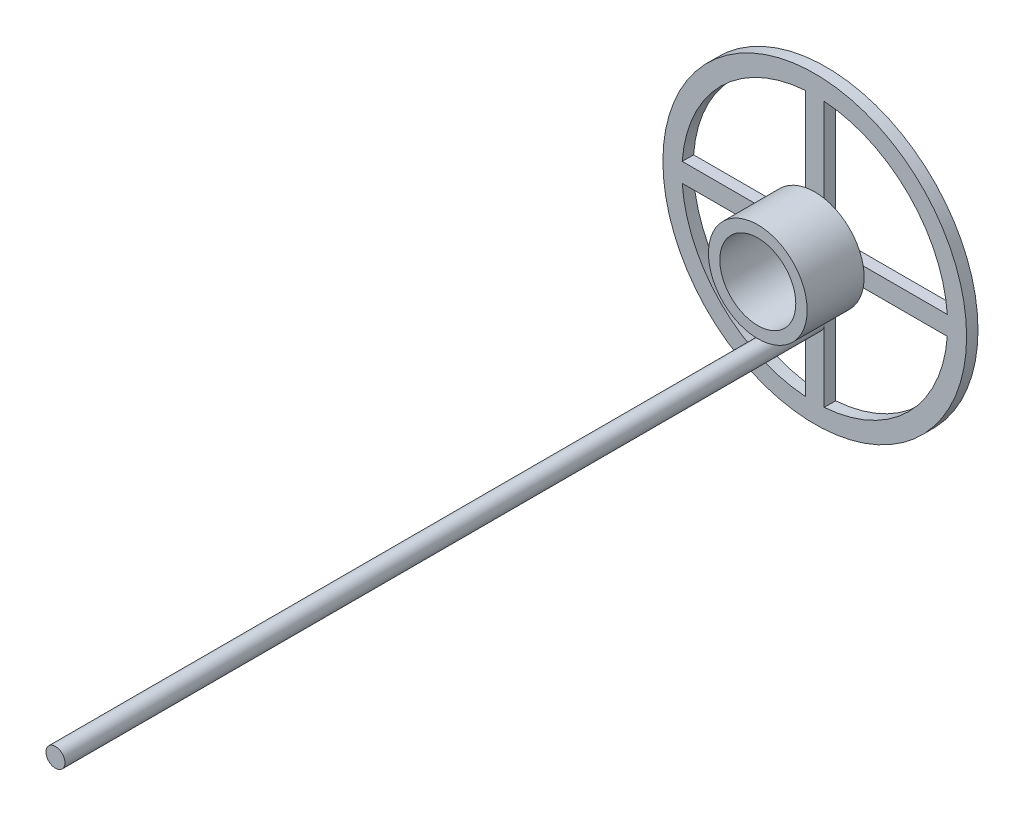
SolidWorks part; units mm, degrees
ref_plane "Alzado" through (0, 0, 0) normal (1, 0, 0) x (0, 1, 0)
ref_plane "Planta" through (0, 0, 0) normal (0, 0, 1) x (0, 1, 0)
ref_plane "Vista lateral" through (0, 0, 0) normal (0, 1, 0) x (-1, 0, 0)
sketch "Croquis1" plane through (0, 0, 0) normal (0, 0, 1) x (0, 1, 0)
  line L0 (25, -25) -> (349.106, -25)
  line L1 (-349.106, 25) -> (-25, 25)
  line L3 (-349.106, -25) -> (-25, -25)
  line L5 (-400, 0) -> (400, 0) construction
  line L6 (0, 400) -> (0, -400) construction
  line L8 (25, -349.106) -> (25, -25)
  line L10 (-25, -349.106) -> (-25, -25)
  line L16 (25, 25) -> (25, 349.106)
  line L19 (-25, 25) -> (-25, 349.106)
  line L24 (25, 25) -> (349.106, 25)
  arc A0 (25, -349.106) -> (349.106, -25) centre (0, 0) ccw
  circle A1 centre (0, 0) radius 400
  circle A2 centre (0, 0) radius 350 construction
  arc A3 (-349.106, -25) -> (-25, -349.106) centre (0, 0) ccw
  arc A4 (349.106, 25) -> (25, 349.106) centre (0, 0) ccw
  arc A5 (-25, 349.106) -> (-349.106, 25) centre (0, 0) ccw
  dimension "D3" = 800
  dimension "D2" = 50
  dimension "D4" = 50
  dimension "D1" = 50
extrude "Saliente-Extruir1" add sketch "Croquis1" along normal blind 30
sketch "Croquis2" plane through (0, 0, 30) normal (0, 0, 1) x (1, 0, 0)
  circle A0 centre (0, 0) radius 100
  circle A1 centre (0, 0) radius 130
  dimension "D1" = 200
  dimension "D2" = 30
extrude "Saliente-Extruir2" add sketch "Croquis2" along normal blind 150
sketch "Croquis3" plane through (0, 0, 30) normal (0, 0, 1) x (1, 0, 0)
  circle A0 centre (0, -160) radius 25
  point P2 (0, 17.3514)
  point P4 (0, -160.7699)
  dimension "D1" = 50
  dimension "D2" = 160
extrude "Saliente-Extruir3" add sketch "Croquis3" along normal blind 2000 separate body
